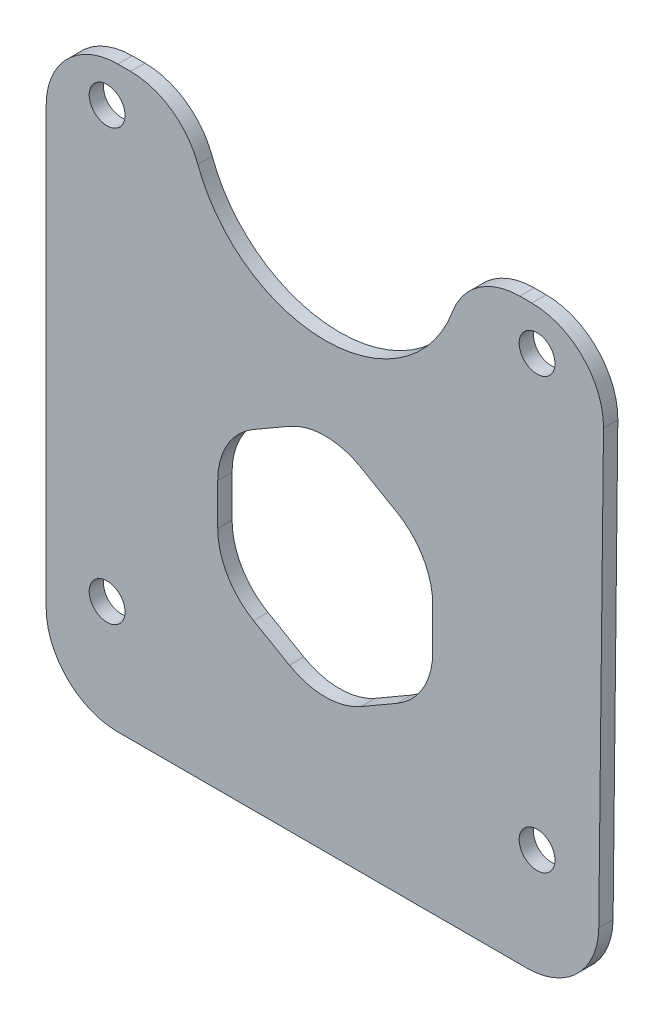
SolidWorks part; units mm, degrees
ref_plane "Front Plane" through (0, 0, 0) normal (0, 0, 1) x (1, 0, 0)
ref_plane "Top Plane" through (0, 0, 0) normal (0, 1, 0) x (1, 0, 0)
ref_plane "Right Plane" through (0, 0, 0) normal (1, 0, 0) x (0, 0, -1)
sketch "Sketch1" plane through (0, 0, 0) normal (0, 0, 1) x (1, 0, 0)
  line L1 (0, 0) -> (117, 0)
  line L2 (0, 0) -> (0, 200)
  line L3 (0, 200) -> (117, 200)
  line L4 (117, 0) -> (117, 200)
  dimension "D1" = 200
  dimension "D2" = 117
extrude "Boss-Extrude1" add sketch "Sketch1" along normal blind 2
sketch "Sketch2" plane through (0, 0, 2) normal (0, 0, 1) x (1, 0, 0)
  line L0 (0, 120) -> (117, 120) construction
  line L1 (0, 200) -> (0, 0) construction
  line L2 (117, 0) -> (117, 200) construction
  line L3 (0, 0) -> (117, 0) construction
  line L4 (0, 120) -> (40, 200)
  line L5 (117, 200) -> (0, 200) construction
  line L7 (77, 200) -> (117, 120)
  line L8 (40, 200) -> (0, 200)
  line L9 (0, 200) -> (0, 120)
  line L10 (77, 200) -> (117, 200)
  line L11 (117, 200) -> (117, 120)
  dimension "D1" = 120
  dimension "D2" = 40
  dimension "D3" = 40
extrude "Cut-Extrude1" cut sketch "Sketch2" against normal blind 2
sketch "Sketch3" plane through (0, 0, 2) normal (0, 0, 1) x (1, 0, 0)
  line L0 (58.5, 200) -> (58.5, 0) construction
  line L1 (77, 200) -> (40, 200) construction
  line L2 (0, 0) -> (117, 0) construction
  line L3 (0, 15) -> (117, 15) construction
  line L4 (48.5, 140) -> (68.5, 140) construction
  line L5 (48.5, 140) -> (48.5, 180) construction
  line L6 (48.5, 180) -> (68.5, 180) construction
  line L7 (68.5, 140) -> (68.5, 180) construction
  line L8 (48.5, 140) -> (68.5, 180) construction
  line L9 (48.5, 180) -> (68.5, 140) construction
  line L10 (0, 120) -> (0, 0) construction
  line L11 (117, 0) -> (117, 120) construction
  line L12 (0, 75) -> (117, 75) construction
  line L14 (36.5, 75) -> (80.5, 75) construction
  line L15 (36.5, 75) -> (36.5, 119) construction
  line L16 (36.5, 119) -> (80.5, 119) construction
  line L17 (80.5, 75) -> (80.5, 119) construction
  line L18 (36.5, 75) -> (80.5, 119) construction
  line L19 (36.5, 119) -> (80.5, 75) construction
  line L24 (0, 25) -> (117, 25) construction
  line L25 (0, 25) -> (0, 65) construction
  line L26 (0, 65) -> (117, 65) construction
  line L27 (117, 25) -> (117, 65) construction
  line L28 (0, 25) -> (117, 65) construction
  line L29 (0, 65) -> (117, 25) construction
  line L34 (43, 81.5) -> (74, 112.5) construction
  line L35 (43, 112.5) -> (74, 81.5) construction
  circle A0 centre (58.5, 170) radius 2.5
  circle A1 centre (58.5, 150) radius 2.5
  circle A2 centre (28.5, 15) radius 2.5
  circle A3 centre (88.5, 15) radius 2.5
  circle A4 centre (28.5, 75) radius 2.5
  circle A5 centre (88.5, 75) radius 2.5
  circle A6 centre (43, 112.5) radius 1.5
  circle A7 centre (43, 81.5) radius 1.5
  circle A8 centre (74, 81.5) radius 1.5
  circle A9 centre (74, 112.5) radius 1.5
  circle A10 centre (58.5, 97) radius 12.5
  point P6 (58.5, 160)
  point P19 (58.5, 97)
  point P28 (58.5, 45)
  point P29 (58.5, 45)
  point P42 (58.5, 97)
  dimension "D6" = 5
  dimension "D7" = 5
  dimension "D14" = 5
  dimension "D15" = 5
  dimension "D16" = 5
  dimension "D17" = 5
  dimension "D22" = 3
  dimension "D23" = 3
  dimension "D24" = 3
  dimension "D25" = 3
  dimension "D31" = 25
  dimension "D1" = 20
  dimension "D2" = 40
  dimension "D3" = 20
  dimension "D4" = 20
  dimension "D5" = 10
  dimension "D8" = 40
  dimension "D9" = 10
  dimension "D10" = 15
  dimension "D11" = 10
  dimension "D12" = 60
  dimension "D13" = 30
  dimension "D18" = 60
  dimension "D19" = 30
  dimension "D20" = 44
  dimension "D21" = 44
  dimension "D26" = 0
  dimension "D27" = 31
  dimension "D28" = 31
  dimension "D29" = 31
  dimension "D30" = 15.5
extrude "Cut-Extrude2" cut sketch "Sketch3" against normal blind 30 contours A10 | A6 | A9 | A8 | A7 | A4 | A5 | A3 | A2 | A0 | A1
fillet "Fillet1" radius 20 6 edges at (40, 200, 1) (77, 200, 1) (117, 120, 1) (0, 120, 1) (0, 0, 1) (117, 0, 1)
sketch "Sketch4" plane through (0, 0, 0) normal (0, 0, -1) x (-1, 0, 0)
  line L0 (-97, 0) -> (-98.7082, 156.5836)
  line L1 (-82.5279, 188.9443) -> (-114.8885, 124.2229) construction
  line L3 (-2.1115, 124.2229) -> (-34.4721, 188.9443) construction
  line L4 (-20, 0) -> (-20, 160)
  line L5 (-20, 160) -> (-18.2918, 156.5836)
  line L10 (-2.1115, 124.2229) -> (-34.4721, 188.9443)
  line L11 (-52.3607, 200) -> (-64.6393, 200)
  line L12 (-82.5279, 188.9443) -> (-114.8885, 124.2229)
  line L13 (-117, 115.2786) -> (-117, 20)
  line L14 (-97, 0) -> (-20, 0)
  line L15 (0, 20) -> (0, 115.2786)
  line L16 (-2.1115, 124.2229) -> (-18.2918, 156.5836)
  line L18 (-98.7082, 156.5836) -> (-114.8885, 124.2229)
  line L19 (-117, 115.2786) -> (-117, 20)
  line L21 (0, 20) -> (0, 115.2786)
  arc A0 (-20, 0) -> (0, 20) centre (-20, 20) ccw construction
  arc A7 (-34.4721, 188.9443) -> (-52.3607, 200) centre (-52.3607, 180) ccw
  arc A8 (-64.6393, 200) -> (-82.5279, 188.9443) centre (-64.6393, 180) ccw
  arc A9 (-114.8885, 124.2229) -> (-117, 115.2786) centre (-97, 115.2786) ccw
  arc A10 (-117, 20) -> (-97, 0) centre (-97, 20) ccw
  arc A11 (-20, 0) -> (0, 20) centre (-20, 20) ccw
  arc A12 (0, 115.2786) -> (-2.1115, 124.2229) centre (-20, 115.2786) ccw
  arc A15 (-114.8885, 124.2229) -> (-117, 115.2786) centre (-97, 115.2786) ccw
  arc A16 (-117, 20) -> (-97, 0) centre (-97, 20) ccw
  arc A17 (-20, 0) -> (0, 20) centre (-20, 20) ccw
  arc A18 (0, 115.2786) -> (-2.1115, 124.2229) centre (-20, 115.2786) ccw
  dimension "D1" = 0
extrude "Cut-Extrude3" cut sketch "Sketch4" against normal blind 10
fillet "Fillet2" radius 10 4 edges at (20, 160, 1) (20, 0, 1) (97, 0, 1) (98.7082, 156.5836, 1)
sketch "Sketch5" plane through (0, 0, 0) normal (0, 0, -1) x (-1, 0, 0)
  line L1 (-97.1079, 9.8909) -> (-98.6818, 154.1654) construction
  line L2 (-20, 157.6393) -> (-20, 10) construction
  line L3 (-97.8806, 80.7177) -> (-77.8806, 80.7177)
  line L4 (-20, 80.7177) -> (-20, 83.8197)
  line L5 (-97.8806, 80.7177) -> (-97.8949, 82.0282)
  line L6 (-40, 80.7177) -> (-20, 80.7177)
  line L9 (-20, 10) -> (-20, 157.6393)
  line L10 (-21.0557, 162.1115) -> (-34.4721, 188.9443)
  line L11 (-52.3607, 200) -> (-64.6393, 200)
  line L12 (-82.5279, 188.9443) -> (-97.6267, 158.7466)
  line L13 (-98.6818, 154.1654) -> (-97.1079, 9.8909)
  line L14 (-87.1085, 0) -> (-30, 0)
  line L15 (-20, 83.8197) -> (-20, 157.6393)
  line L16 (-21.0557, 162.1115) -> (-34.4721, 188.9443)
  line L17 (-52.3607, 200) -> (-64.6393, 200)
  line L18 (-82.5279, 188.9443) -> (-97.6267, 158.7466)
  line L19 (-98.6818, 154.1654) -> (-97.8949, 82.0282)
  arc A0 (-77.8806, 80.7177) -> (-40, 80.7177) centre (-58.9403, 80.7177) ccw
  arc A6 (-20, 157.6393) -> (-21.0557, 162.1115) centre (-30, 157.6393) ccw
  arc A7 (-34.4721, 188.9443) -> (-52.3607, 200) centre (-52.3607, 180) ccw
  arc A8 (-64.6393, 200) -> (-82.5279, 188.9443) centre (-64.6393, 180) ccw
  arc A9 (-97.6267, 158.7466) -> (-98.6818, 154.1654) centre (-88.6824, 154.2745) ccw
  arc A10 (-97.1079, 9.8909) -> (-87.1085, 0) centre (-87.1085, 10) ccw
  arc A11 (-30, 0) -> (-20, 10) centre (-30, 10) ccw
  arc A12 (-20, 157.6393) -> (-21.0557, 162.1115) centre (-30, 157.6393) ccw
  arc A13 (-34.4721, 188.9443) -> (-52.3607, 200) centre (-52.3607, 180) ccw
  arc A14 (-64.6393, 200) -> (-82.5279, 188.9443) centre (-64.6393, 180) ccw
  arc A15 (-97.6267, 158.7466) -> (-98.6818, 154.1654) centre (-88.6824, 154.2745) ccw
  dimension "D3" = 20
  dimension "D4" = 20
  dimension "D1" = 0
extrude "Cut-Extrude4" cut sketch "Sketch5" against normal blind 10
fillet "Fillet3" radius 10 4 edges at (20, 80.7177, 1) (97.8806, 80.7177, 1) (40, 80.7177, 1) (77.8806, 80.7177, 1)
sketch "Sketch6" plane through (0, 0, 0) normal (0, 0, -1) x (-1, 0, 0)
  line L0 (-58.9403, 61.7774) -> (-58.9403, 0) construction
  line L1 (-30, 0) -> (-87.1085, 0) construction
  line L3 (-58.9403, 51.7949) -> (-73.9403, 43.1346)
  line L4 (-73.9403, 43.1346) -> (-73.9403, 25.8141)
  line L5 (-73.9403, 25.8141) -> (-58.9403, 17.1538)
  line L6 (-58.9403, 17.1538) -> (-43.9403, 25.8141)
  line L7 (-43.9403, 25.8141) -> (-43.9403, 43.1346)
  line L8 (-43.9403, 43.1346) -> (-58.9403, 51.7949)
  arc A0 (-76.7139, 74.1731) -> (-41.1666, 74.1731) centre (-58.9403, 80.7177) ccw construction
  circle A1 centre (-58.9403, 34.4743) radius 15 construction
  dimension "D1" = 30
extrude "Cut-Extrude5" cut sketch "Sketch6" against normal blind 10
fillet "Fillet4" radius 10 6 edges at (43.9403, 43.1346, 1) (43.9403, 25.8141, 1) (58.9403, 17.1538, 1) (73.9403, 25.8141, 1) (73.9403, 43.1346, 1) (58.9403, 51.7949, 1)
